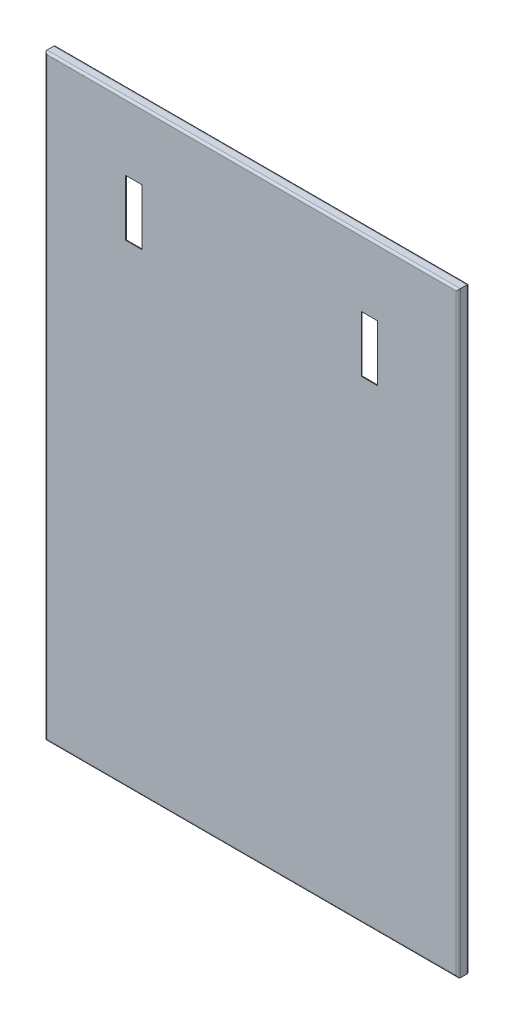
SolidWorks part; units mm, degrees
ref_plane "정면" through (0, 0, 0) normal (0, 0, 1) x (1, 0, 0)
ref_plane "윗면" through (0, 0, 0) normal (0, 1, 0) x (1, 0, 0)
ref_plane "우측면" through (0, 0, 0) normal (1, 0, 0) x (0, 0, -1)
sketch "스케치1" plane through (0, 0, 0) normal (0, 0, 1) x (1, 0, 0)
  line L1 (0, 0) -> (640, 0)
  line L2 (0, 0) -> (0, 924)
  line L3 (0, 924) -> (640, 924)
  line L4 (640, 0) -> (640, 924)
  line L5 (125, 820) -> (150, 820)
  line L6 (125, 820) -> (125, 733)
  line L7 (125, 733) -> (150, 733)
  line L8 (150, 820) -> (150, 733)
  line L9 (490, 820) -> (515, 820)
  line L10 (490, 820) -> (490, 733)
  line L11 (490, 733) -> (515, 733)
  line L12 (515, 820) -> (515, 733)
  point P14 (150, 776.5)
  dimension "D1" = 924
  dimension "D2" = 640
  dimension "D3" = 125
  dimension "D4" = 25
  dimension "D5" = 340
  dimension "D6" = 25
  dimension "D7" = 87
  dimension "D8" = 733
extrude "보스-돌출1" add sketch "스케치1" along normal blind 1.2
sketch "스케치2" plane through (0, 0, 0) normal (0, 0, -1) x (-1, 0, 0)
  line L0 (-1.2, 922.8) -> (-638.8, 922.8)
  line L1 (-638.8, 922.8) -> (-638.8, 1.2)
  line L2 (-638.8, 1.2) -> (-1.2, 1.2)
  line L3 (-1.2, 1.2) -> (-1.2, 922.8)
  line L4 (0, 0) -> (0, 924)
  line L5 (0, 924) -> (-640, 924)
  line L6 (-640, 924) -> (-640, 0)
  line L7 (-640, 0) -> (0, 0)
  line L8 (0, 0) -> (0, 924)
  line L9 (0, 924) -> (-640, 924)
  line L10 (-640, 924) -> (-640, 0)
  line L11 (-640, 0) -> (0, 0)
  dimension "D1" = 0
  dimension "D2" = 1.2
extrude "보스-돌출2" add sketch "스케치2" along normal blind 15.5
sketch "스케치3" plane through (0, 0, -15.5) normal (0, 0, -1) x (-1, 0, 0)
  line L0 (-15, 909) -> (-625, 909)
  line L1 (-625, 909) -> (-625, 15)
  line L2 (-625, 15) -> (-15, 15)
  line L3 (-15, 15) -> (-15, 909)
  line L4 (-640, 0) -> (0, 0)
  line L5 (0, 0) -> (0, 924)
  line L6 (0, 924) -> (-640, 924)
  line L7 (-640, 924) -> (-640, 0)
  line L8 (-640, 0) -> (0, 0)
  line L9 (0, 0) -> (0, 924)
  line L10 (0, 924) -> (-640, 924)
  line L11 (-640, 924) -> (-640, 0)
  dimension "D1" = 0
  dimension "D2" = 15
extrude "보스-돌출3" add sketch "스케치3" against normal blind 1.2
fillet "필렛1" radius 2 12 edges at (638.8, 462, 0) (638.8, 462, -14.3) (320, 1.2, 0) (320, 1.2, -14.3) (638.8, 1.2, -7.15) (1.2, 462, 0) (1.2, 462, -14.3) (1.2, 1.2, -7.15) (320, 922.8, 0) (638.8, 922.8, -7.15) (320, 922.8, -14.3) (1.2, 922.8, -7.15)
fillet "필렛2" radius 3.2 4 edges at (320, 924, 1.2) (320, 0, 1.2) (0, 462, 1.2) (640, 462, 1.2)
fillet "필렛3" radius 3.2 4 edges at (640, 462, -15.5) (320, 924, -15.5) (0, 462, -15.5) (320, 0, -15.5)
